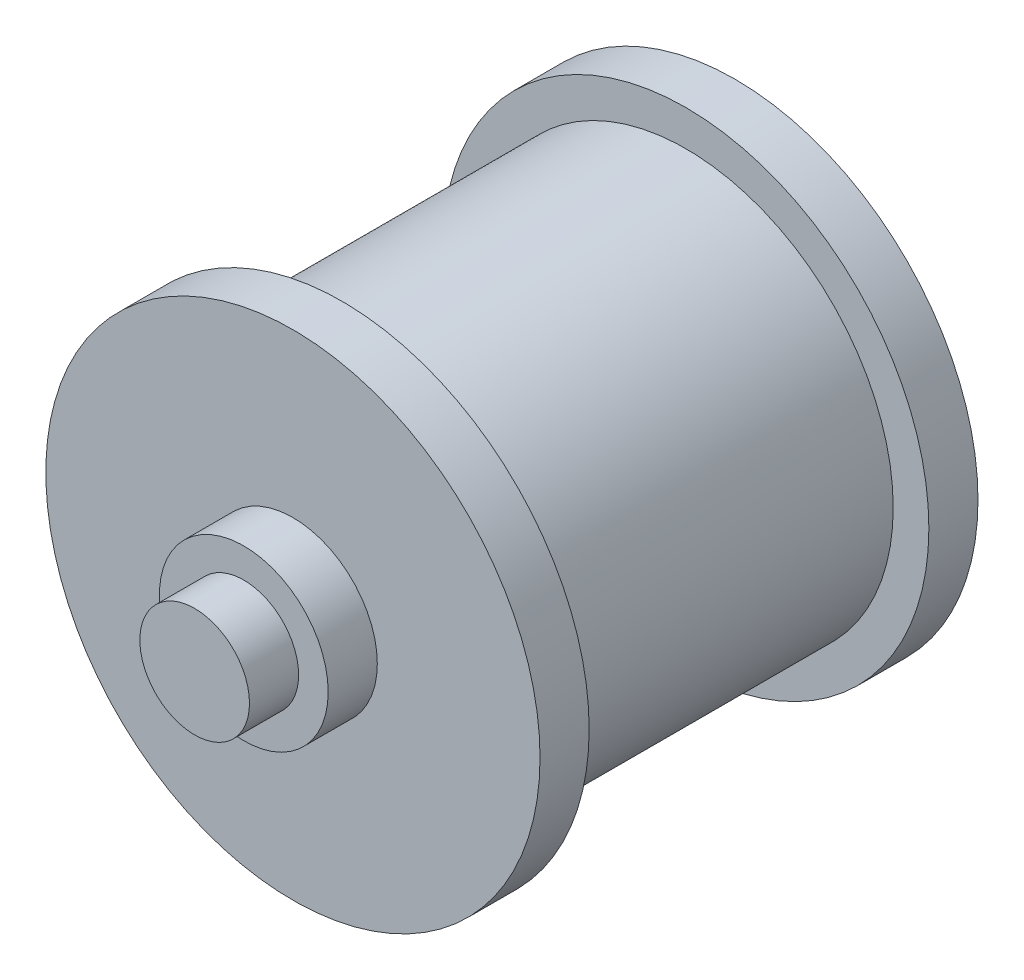
SolidWorks part; units mm, degrees
ref_plane "Front Plane" through (0, 0, 0) normal (0, 0, 1) x (1, 0, 0)
ref_plane "Top Plane" through (0, 0, 0) normal (0, 1, 0) x (1, 0, 0)
ref_plane "Right Plane" through (0, 0, 0) normal (1, 0, 0) x (0, 0, -1)
sketch "Sketch1" plane through (0, 0, 0) normal (0, 0, 1) x (1, 0, 0)
  circle A1 centre (0, 0) radius 49.4443
extrude "Boss-Extrude1" add sketch "Sketch1" along normal blind 10
sketch "Sketch4" plane through (0, 0, 10) normal (0, 0, 1) x (1, 0, 0)
  circle A0 centre (0, 0) radius 42.1864
extrude "Boss-Extrude2" add sketch "Sketch4" along normal blind 70
sketch "Sketch5" plane through (0, 0, 80) normal (0, 0, 1) x (1, 0, 0)
  circle A0 centre (0, 0) radius 50.2995
extrude "Boss-Extrude3" add sketch "Sketch5" along normal blind 10
sketch "Sketch6" plane through (0, 0, 0) normal (0, 0, -1) x (-1, 0, 0)
  circle A0 centre (0, 0) radius 13.6957
extrude "Boss-Extrude4" add sketch "Sketch6" along normal blind 10
sketch "Sketch7" plane through (0, 0, -10) normal (0, 0, -1) x (-1, 0, 0)
  circle A0 centre (0, 0) radius 9.1937
extrude "Boss-Extrude5" add sketch "Sketch7" along normal blind 10
sketch "Sketch8" plane through (0, 0, 90) normal (0, 0, 1) x (1, 0, 0)
  circle A0 centre (0, 0) radius 17.1767
extrude "Boss-Extrude6" add sketch "Sketch8" along normal blind 10
sketch "Sketch9" plane through (0, 0, 100) normal (0, 0, 1) x (1, 0, 0)
  circle A0 centre (0, 0) radius 11.1575
extrude "Boss-Extrude7" add sketch "Sketch9" along normal blind 10
scale "Scale1" scale about centroid uniform scaling yes scale factor 0.9
scale "Scale2" scale about centroid uniform scaling yes scale factor 0.7
